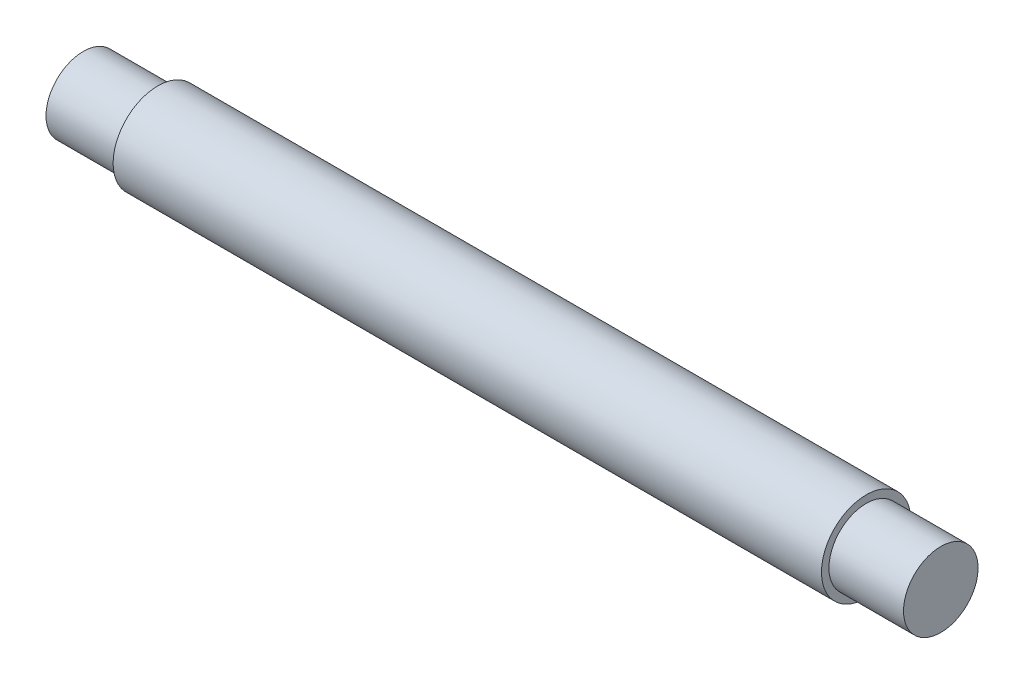
SolidWorks part; units mm, degrees
ref_plane "Front Plane" through (0, 0, 0) normal (0, 0, 1) x (1, 0, 0)
ref_plane "Top Plane" through (0, 0, 0) normal (0, 1, 0) x (1, 0, 0)
ref_plane "Right Plane" through (0, 0, 0) normal (1, 0, 0) x (0, 0, -1)
sketch "Sketch1" plane through (0, 0, 0) normal (0, 1, 0) x (1, 0, 0)
  line L0 (0, 0) -> (115, 0) construction
  line L1 (115, 0) -> (115, 5)
  line L2 (115, 5) -> (105, 5)
  line L3 (105, 5) -> (105, 6)
  line L4 (105, 6) -> (10, 6)
  line L5 (10, 6) -> (10, 5)
  line L6 (10, 5) -> (0, 5)
  line L7 (0, 5) -> (0, 0)
  line L8 (0, 0) -> (115, 0)
  dimension "D1" = 115
  dimension "D2" = 10
  dimension "D3" = 10
  dimension "D4" = 12
  dimension "D5" = 10
revolve "Revolve1" add sketch "Sketch1" angle 360 about L0
cosmetic thread "Cosmetic Thread1" parameters "D1"=10, "D2"=8.344
cosmetic thread "Cosmetic Thread2" parameters "D1"=10, "D2"=8.344
